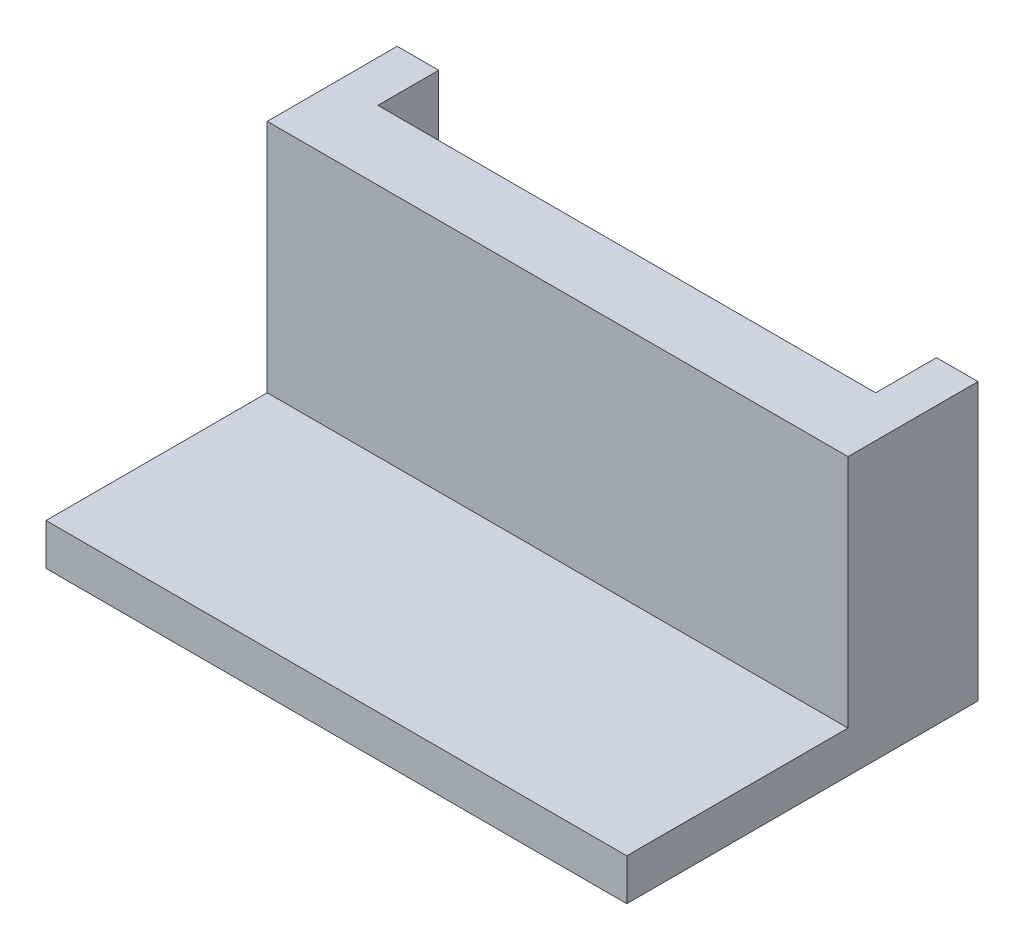
SolidWorks part; units mm, degrees
ref_plane "Front Plane" through (0, 0, 0) normal (0, 0, 1) x (1, 0, 0)
ref_plane "Top Plane" through (0, 0, 0) normal (0, 1, 0) x (1, 0, 0)
ref_plane "Right Plane" through (0, 0, 0) normal (1, 0, 0) x (0, 0, -1)
sketch "Sketch1" plane through (0, 0, 0) normal (0, 1, 0) x (1, 0, 0)
  line L1 (-3.0815, 1.5021) -> (14.9185, 1.5021)
  line L2 (-3.0815, 1.5021) -> (-3.0815, -3.1979)
  line L3 (-3.0815, -3.1979) -> (14.9185, -3.1979)
  line L4 (14.9185, 1.5021) -> (14.9185, -3.1979)
  dimension "D1" = 18
  dimension "D2" = 4.7
extrude "Boss-Extrude1" add sketch "Sketch1" along normal blind 1.5 contours L1 L4 L3 L2
sketch "Sketch2" plane through (0, 1.5, 0) normal (0, 1, 0) x (1, 0, 0)
  line L1 (-3.0815, 1.5021) -> (1.9185, 1.5021)
  line L2 (-3.0815, 1.5021) -> (-3.0815, 0.6021)
  line L3 (-3.0815, 0.6021) -> (1.9185, 0.6021)
  line L4 (1.9185, 1.5021) -> (1.9185, 0.6021)
  line L5 (14.9185, 1.5021) -> (14.9185, -3.1979) construction
  line L6 (14.9185, 1.5021) -> (9.9185, 1.5021)
  line L7 (14.9185, 1.5021) -> (14.9185, 0.6021)
  line L8 (14.9185, 0.6021) -> (9.9185, 0.6021)
  line L9 (9.9185, 1.5021) -> (9.9185, 0.6021)
  line L10 (-3.0815, -3.1979) -> (14.9185, -3.1979)
  line L11 (-3.0815, -3.1979) -> (-3.0815, -0.6979)
  line L12 (-3.0815, -0.6979) -> (14.9185, -0.6979)
  line L13 (14.9185, -3.1979) -> (14.9185, -0.6979)
  dimension "D1" = 5
  dimension "D2" = 0.9
  dimension "D3" = 5
  dimension "D4" = 2.5
  dimension "D5" = 0.9
extrude "Boss-Extrude2" add sketch "Sketch2" along normal blind 4.5
sketch "Sketch3" plane through (0, 6, 0) normal (0, 1, 0) x (1, 0, 0)
  line L1 (-3.0815, -0.6979) -> (14.9185, -0.6979)
  line L2 (-3.0815, -0.6979) -> (-3.0815, -3.1979)
  line L3 (-3.0815, -3.1979) -> (14.9185, -3.1979)
  line L4 (14.9185, -0.6979) -> (14.9185, -3.1979)
extrude "Boss-Extrude3" add sketch "Sketch3" along normal blind 4
sketch "Sketch4" plane through (14.9185, 0, 0) normal (1, 0, 0) x (0, 0, -1)
  line L1 (-3.1979, 10) -> (1.5021, 10)
  line L2 (-3.1979, 10) -> (-3.1979, 0)
  line L3 (-3.1979, 0) -> (1.5021, 0)
  line L4 (1.5021, 10) -> (1.5021, 0)
extrude "Boss-Extrude4" add sketch "Sketch4" along normal blind 1.5
sketch "Sketch5" plane through (-3.0815, 0, 0) normal (-1, 0, 0) x (0, 0, 1)
  line L1 (3.1979, 10) -> (-1.5021, 10)
  line L2 (3.1979, 10) -> (3.1979, 0)
  line L3 (3.1979, 0) -> (-1.5021, 0)
  line L4 (-1.5021, 10) -> (-1.5021, 0)
extrude "Boss-Extrude5" add sketch "Sketch5" along normal blind 1.5
sketch "Sketch6" plane through (0, 0, 3.1979) normal (0, 0, 1) x (1, 0, 0)
  line L0 (16.4185, 10) -> (16.4185, 0) construction
  line L1 (-4.5815, 0) -> (16.4185, 0)
  line L2 (-4.5815, 0) -> (-4.5815, 1.5)
  line L3 (-4.5815, 1.5) -> (16.4185, 1.5)
  line L4 (16.4185, 0) -> (16.4185, 1.5)
  dimension "D1" = 1.5
extrude "Boss-Extrude6" add sketch "Sketch6" along normal blind 8
